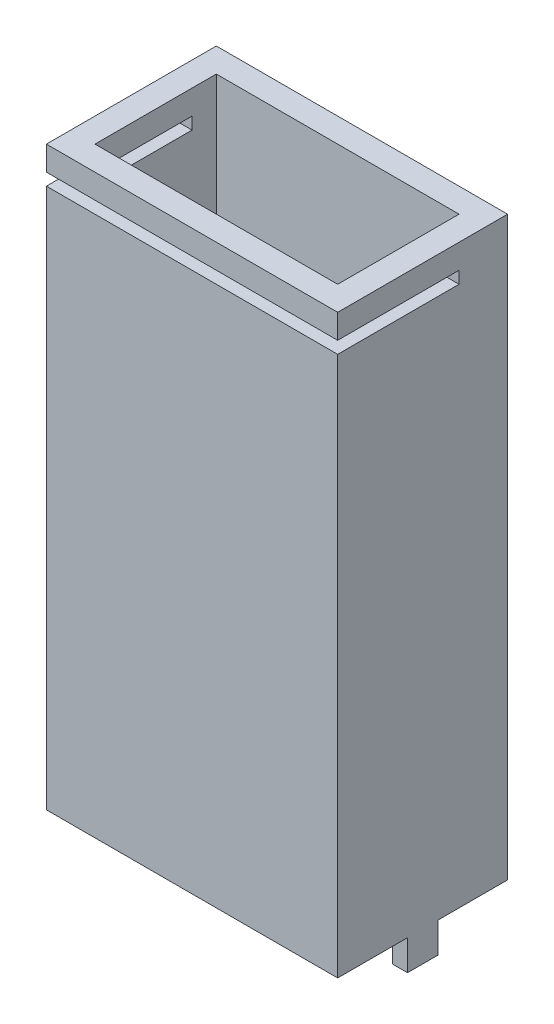
SolidWorks part; units mm, degrees
ref_plane "Front Plane" through (0, 0, 0) normal (0, 0, 1) x (1, 0, 0)
ref_plane "Top Plane" through (0, 0, 0) normal (0, 1, 0) x (1, 0, 0)
ref_plane "Right Plane" through (0, 0, 0) normal (1, 0, 0) x (0, 0, -1)
sketch "Sketch1" plane through (0, 0, 0) normal (0, 1, 0) x (1, 0, 0)
  line L0 (-4, 4) -> (44, 4)
  line L1 (0, 0) -> (40, 0)
  line L2 (0, 0) -> (0, -20)
  line L3 (0, -20) -> (40, -20)
  line L4 (40, 0) -> (40, -20)
  line L5 (44, 4) -> (44, -24)
  line L6 (-4, -24) -> (44, -24)
  line L7 (-4, 4) -> (-4, -24)
  dimension "D1" = 40
  dimension "D2" = 20
  dimension "D3" = 4
extrude "Boss-Extrude1" add sketch "Sketch1" along normal blind 95
sketch "Sketch6" plane through (0, 0, 0) normal (0, -1, 0) x (1, 0, 0)
  line L0 (-4, -4) -> (-4, 24) construction
  line L1 (-4, 12.5) -> (-1.5, 12.5)
  line L2 (-4, 12.5) -> (-4, 7.5)
  line L3 (-4, 7.5) -> (-1.5, 7.5)
  line L4 (-1.5, 12.5) -> (-1.5, 7.5)
  line L7 (41.5, 12.5) -> (44, 12.5)
  line L8 (41.5, 12.5) -> (41.5, 7.5)
  line L9 (41.5, 7.5) -> (44, 7.5)
  line L10 (44, 12.5) -> (44, 7.5)
  line L11 (44, -4) -> (44, 24) construction
  line L12 (-4, 24) -> (44, 24) construction
  point P18 (-4, 10)
  dimension "D1" = 14
  dimension "D2" = 5
  dimension "D3" = 2.5
  dimension "D4" = 2.5
extrude "Boss-Extrude3" add sketch "Sketch6" along normal blind 5
sketch "Sketch7" plane through (0, 0, 24) normal (0, 0, 1) x (1, 0, 0)
  line L0 (-4, 95) -> (44, 95) construction
  line L1 (-6.5973, 91) -> (48.7217, 91)
  line L2 (-6.5973, 91) -> (-6.5973, 89)
  line L3 (-6.5973, 89) -> (48.7217, 89)
  line L4 (48.7217, 91) -> (48.7217, 89)
  dimension "D1" = 2
  dimension "D2" = 6
extrude "Cut-Extrude1" cut sketch "Sketch7" against normal blind 20
